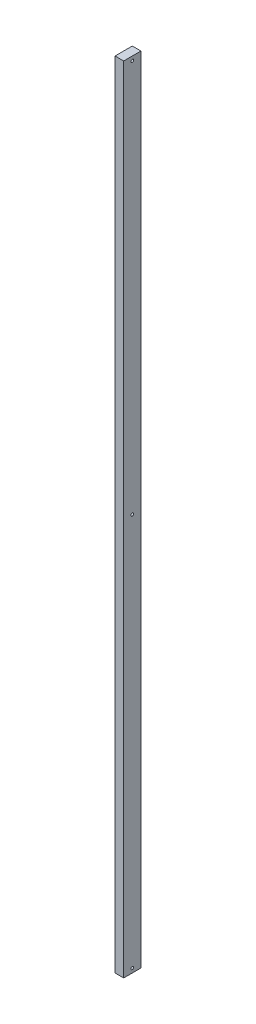
SolidWorks part; units mm, degrees
ref_plane "Спереди" through (0, 0, 0) normal (0, 0, 1) x (1, 0, 0)
ref_plane "Сверху" through (0, 0, 0) normal (0, 1, 0) x (1, 0, 0)
ref_plane "Справа" through (0, 0, 0) normal (1, 0, 0) x (0, 0, -1)
other "Configuration Table"
sketch "Эскиз1" plane through (0, 0, 0) normal (0, 1, 0) x (1, 0, 0)
  line L1 (12.5, 25) -> (-12.5, 25)
  line L2 (12.5, 25) -> (12.5, -25)
  line L3 (12.5, -25) -> (-12.5, -25)
  line L4 (-12.5, 25) -> (-12.5, -25)
  line L5 (12.5, 25) -> (-12.5, -25) construction
  line L6 (12.5, -25) -> (-12.5, 25) construction
  point P0 (0, 0)
extrude "Бобышка-Вытянуть1" add sketch "Эскиз1" along normal blind 2300
sketch "Эскиз2" plane through (12.5, 0, 0) normal (1, 0, 0) x (0, 0, -1)
  line L0 (0, 0) -> (0, 25) construction
  line L1 (-25, 2300) -> (25, 2300) construction
  line L2 (0, 2300) -> (0, 2275) construction
  circle A0 centre (0, 1150) radius 4
  circle A1 centre (0, 2287.5) radius 4
  circle A2 centre (0, 12.5) radius 4
extrude "Вырез-Вытянуть1" cut sketch "Эскиз2" against normal blind 2300
